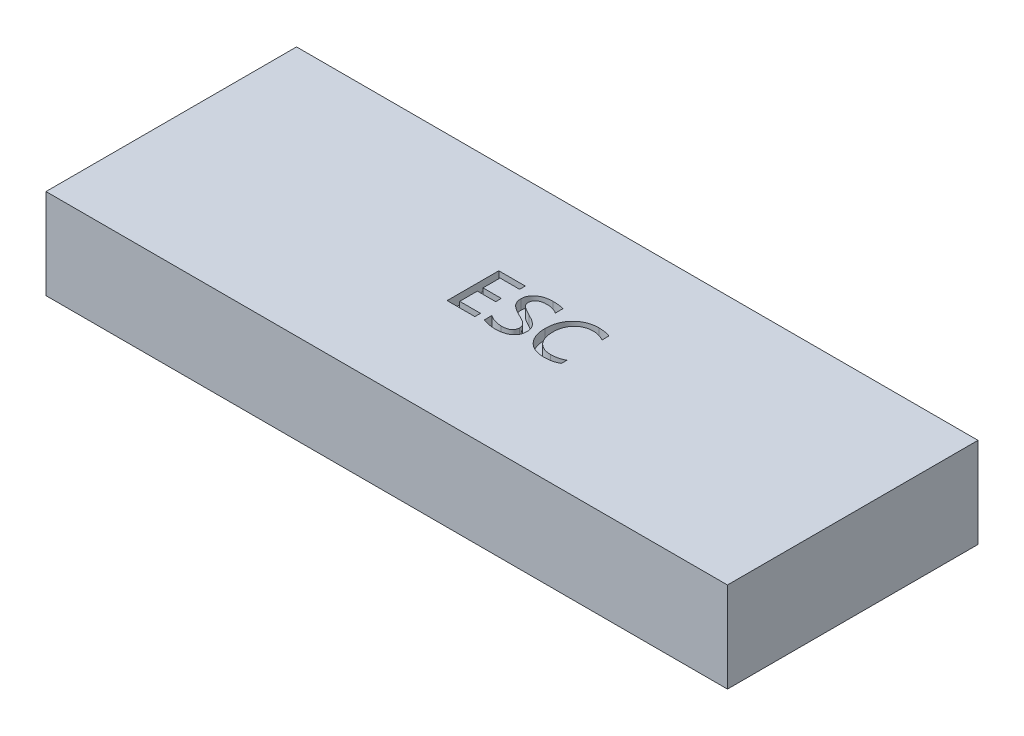
SolidWorks part; units mm, degrees
ref_plane "前视基准面" through (0, 0, 0) normal (0, 0, 1) x (1, 0, 0)
ref_plane "上视基准面" through (0, 0, 0) normal (0, 1, 0) x (1, 0, 0)
ref_plane "右视基准面" through (0, 0, 0) normal (1, 0, 0) x (0, 0, -1)
sketch "草图1" plane through (0, 0, 0) normal (0, 1, 0) x (1, 0, 0)
  line L1 (-34, 12.5) -> (34, 12.5)
  line L2 (-34, 12.5) -> (-34, -12.5)
  line L3 (-34, -12.5) -> (34, -12.5)
  line L4 (34, 12.5) -> (34, -12.5)
  line L5 (-34, 12.5) -> (34, -12.5) construction
  line L6 (-34, -12.5) -> (34, 12.5) construction
  point P0 (0, 0)
  dimension "D1" = 68
  dimension "D2" = 25
extrude "凸台-拉伸1" add sketch "草图1" along normal blind 9
sketch "草图2" plane through (0, 9, 0) normal (0, 1, 0) x (1, 0, 0)
  text T0 "ESC" font "微软雅黑" height in points 18
  point P1 (0, 0)
  point P2 (-5.1905, -1.9123)
extrude "切除-拉伸1" cut sketch "草图2" against normal blind 1
